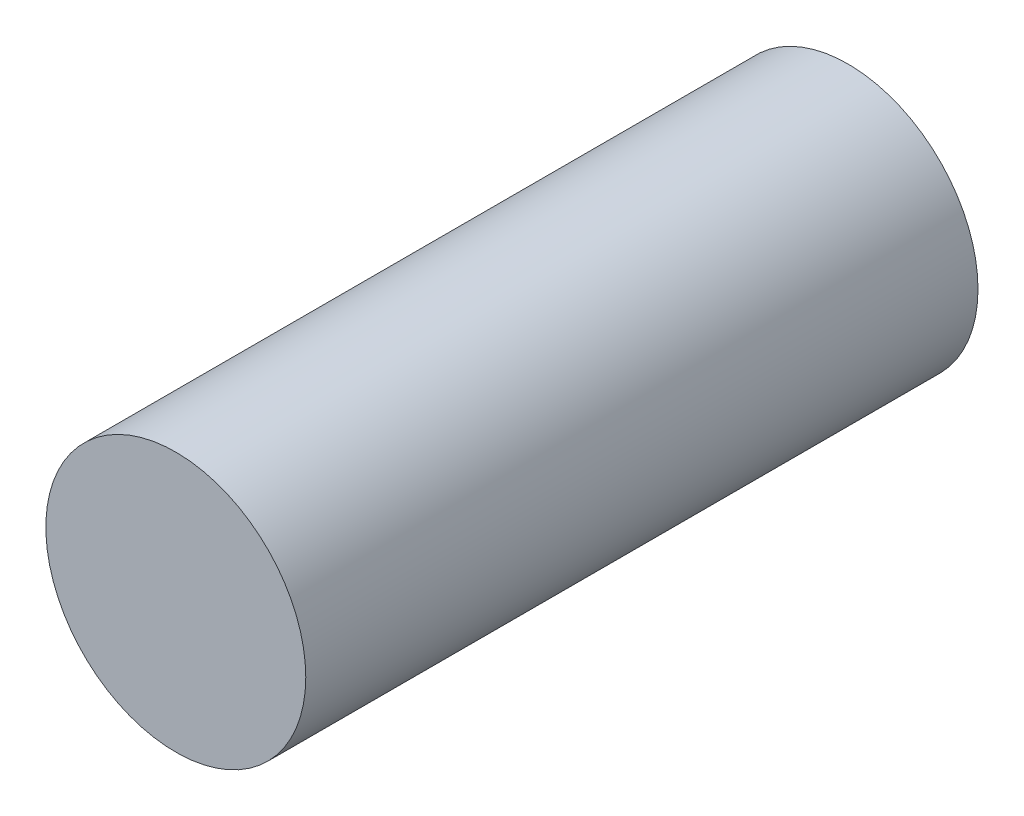
SolidWorks part; units mm, degrees
ref_plane "Спереди" through (0, 0, 0) normal (0, 0, 1) x (1, 0, 0)
ref_plane "Сверху" through (0, 0, 0) normal (0, 1, 0) x (1, 0, 0)
ref_plane "Справа" through (0, 0, 0) normal (1, 0, 0) x (0, 0, -1)
other "Configuration Table"
sketch "Эскиз1" plane through (0, 0, 0) normal (0, 0, 1) x (1, 0, 0)
  line L1 (-30, -20) -> (30, -20) construction
  line L2 (-30, -20) -> (-30, 20) construction
  line L3 (-30, 20) -> (30, 20) construction
  line L4 (30, -20) -> (30, 20) construction
  line L5 (-30, -20) -> (30, 20) construction
  line L6 (-30, 20) -> (30, -20) construction
  circle A0 centre (0, 0) radius 55.5
  circle A1 centre (0, 0) radius 58
  dimension "D1" = 111
  dimension "D2" = 116
  dimension "D3" = 60
  dimension "D4" = 40
extrude "Бобышка-Вытянуть1" add sketch "Эскиз1" along normal mid plane 300
sketch "Эскиз2" plane through (0, 0, 150) normal (0, 0, 1) x (1, 0, 0)
  circle A0 centre (0, 0) radius 58 construction
  circle A2 centre (0, 0) radius 58
extrude "Бобышка-Вытянуть2" add sketch "Эскиз2" against normal blind 10
